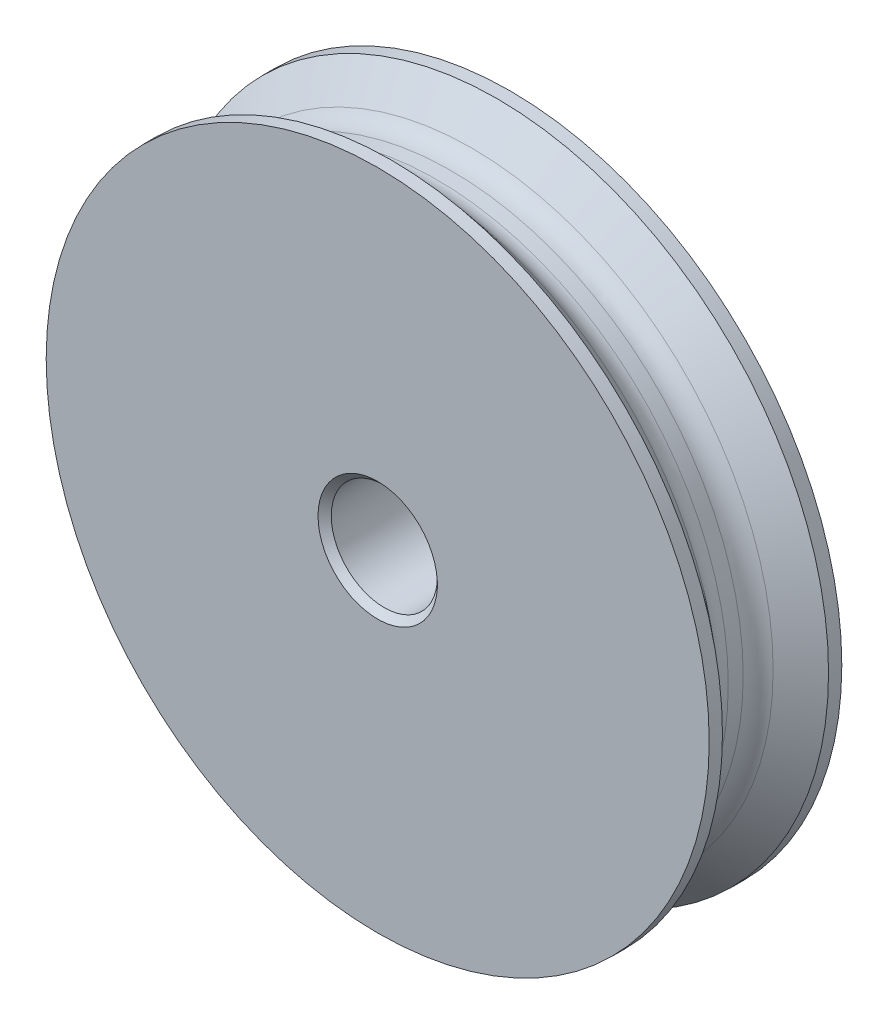
SolidWorks part; units mm, degrees
material "ABS"
ref_plane "Płaszczyzna przednia" through (0, 0, 0) normal (0, 0, 1) x (1, 0, 0)
ref_plane "Płaszczyzna górna" through (0, 0, 0) normal (0, 1, 0) x (1, 0, 0)
ref_plane "Płaszczyzna prawa" through (0, 0, 0) normal (1, 0, 0) x (0, 0, -1)
sketch "Szkic1" plane through (0, 0, 0) normal (1, 0, 0) x (0, 0, -1)
  line L0 (0, 0) -> (8415.5621, 0) construction
  line L1 (0, 0) -> (0, 8415.5621) construction
  line L2 (-5, 4) -> (5, 4)
  line L3 (5, 4) -> (5, 25)
  line L4 (-5, 4) -> (-5, 25)
  line L5 (-5, 25) -> (-4, 25)
  line L6 (-4, 25) -> (-1.5, 22)
  line L7 (-1.5, 22) -> (1.5, 22)
  line L8 (1.5, 22) -> (4, 25)
  line L9 (4, 25) -> (5, 25)
  dimension "D1" = 8
  dimension "D2" = 1
  dimension "D3" = 10
  dimension "D4" = 50
  dimension "D5" = 3
  dimension "D6" = 3
revolve "Obrót1" add sketch "Szkic1" angle 360 about L0
fillet "Zaokrąglenie1" radius 2 2 edges at (22, 0, -1.5) (22, 0, 1.5)
chamfer "Sfazowanie1" distance 0.5 angle 45 2 edges at (4, 0, -5) (4, 0, 5)
